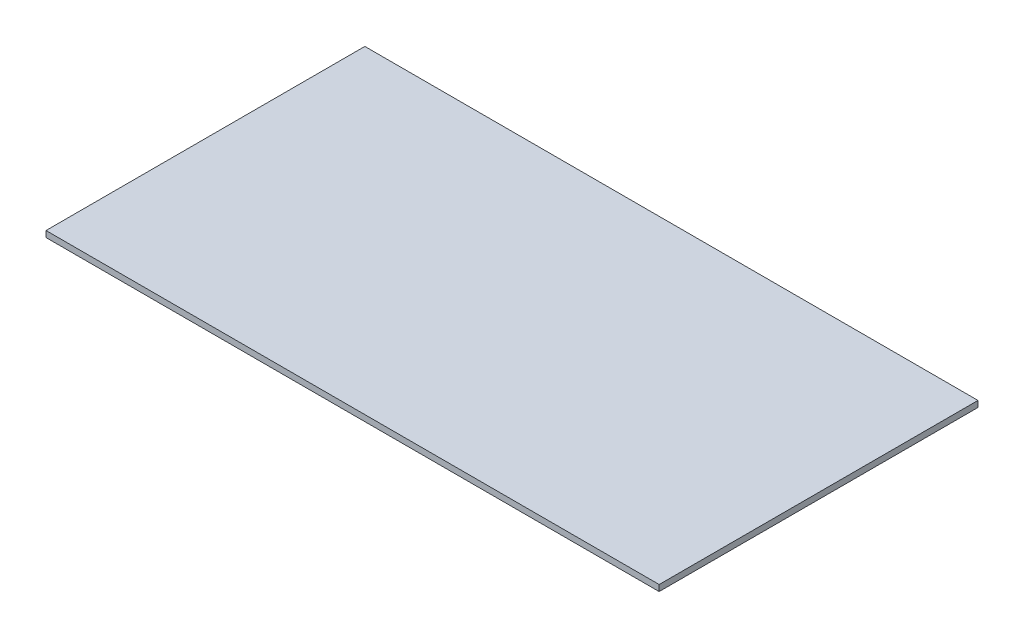
SolidWorks part; units mm, degrees
ref_plane "Front Plane" through (0, 0, 0) normal (0, 0, 1) x (1, 0, 0)
ref_plane "Top Plane" through (0, 0, 0) normal (0, 1, 0) x (1, 0, 0)
ref_plane "Right Plane" through (0, 0, 0) normal (1, 0, 0) x (0, 0, -1)
sketch "Sketch1" plane through (0, 0, 0) normal (0, 1, 0) x (1, 0, 0)
  line L1 (-250, 130) -> (250, 130)
  line L2 (-250, 130) -> (-250, -130)
  line L3 (-250, -130) -> (250, -130)
  line L4 (250, 130) -> (250, -130)
  line L5 (-250, 130) -> (250, -130) construction
  line L6 (-250, -130) -> (250, 130) construction
  point P0 (0, 0)
extrude "Boss-Extrude1" add sketch "Sketch1" along normal blind 5
